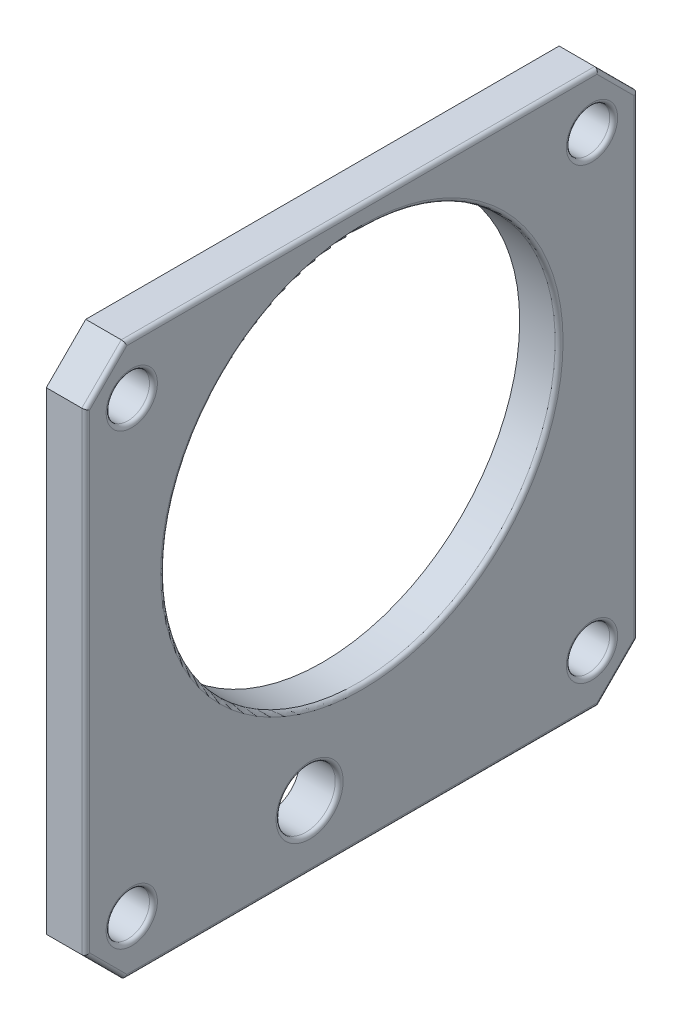
SolidWorks part; units mm, degrees
ref_plane "Front Plane" through (0, 0, 0) normal (0, 0, 1) x (1, 0, 0)
ref_plane "Top Plane" through (0, 0, 0) normal (0, 1, 0) x (1, 0, 0)
ref_plane "Right Plane" through (0, 0, 0) normal (1, 0, 0) x (0, 0, -1)
sketch "Sketch1" plane through (0, 0, 0) normal (1, 0, 0) x (0, 0, -1)
  line L0 (-21, 18) -> (-18, 21)
  line L1 (-18, 21) -> (18, 21)
  line L2 (-21, 18) -> (-21, -18)
  line L3 (-18, -21) -> (18, -21)
  line L4 (21, 18) -> (21, -18)
  line L5 (-21, 21) -> (21, -21) construction
  line L6 (-21, -21) -> (21, 21) construction
  line L7 (18, 21) -> (21, 18)
  line L8 (18, -21) -> (21, -18)
  line L9 (-21, -18) -> (-18, -21)
  circle A1 centre (0, 4.4) radius 15
  circle A2 centre (0, 4.4) radius 13.25 construction
  point P0 (0, 0)
  dimension "D2" = 30
  dimension "D1" = 42
extrude "Boss-Extrude1" add sketch "Sketch1" along normal blind 3
sketch "Sketch2" plane through (0, 0, 0) normal (-1, 0, 0) x (0, 0, 1)
  circle A2 centre (-17.4995, 17.062) radius 1.65 construction
  circle A6 centre (-17.4995, 17.062) radius 1.65
  circle A8 centre (-17.4995, -17.062) radius 1.65 construction
  circle A9 centre (17.4995, -17.062) radius 1.65 construction
  circle A10 centre (17.4995, 17.062) radius 1.65 construction
  circle A11 centre (-17.4995, -17.062) radius 1.65
  circle A12 centre (17.4995, -17.062) radius 1.65
  circle A13 centre (17.4995, 17.062) radius 1.65
extrude "Cut-Extrude1" cut sketch "Sketch2" against normal through all both and the other way through all
sketch "Sketch4" plane through (0, 0, 0) normal (-1, 0, 0) x (0, 0, 1)
  line L0 (-10.975, -12.2) -> (10.975, -12.2) construction
  line L1 (-10.975, -12.2) -> (10.975, -12.2) construction
  circle A0 centre (3.975, -16.2) radius 2.25
  dimension "D1" = 4.5
  dimension "D2" = 4
  dimension "7" = 7
extrude "Cut-Extrude2" cut sketch "Sketch4" against normal through all
fillet "Fillet1" radius 0.3 14 edges at (3, 4.4, -15) (3, 19.5, -19.5) (3, 0, -21) (3, -19.5, -19.5) (3, -21, 0) (3, -19.5, 19.5) (3, 0, 21) (3, 19.5, 19.5) (3, 21, 0) (3, -17.062, -15.8495) (3, 17.062, 19.1495) (3, 17.062, -15.8495) (3, -17.062, 19.1495) (3, -16.2, 6.225)
